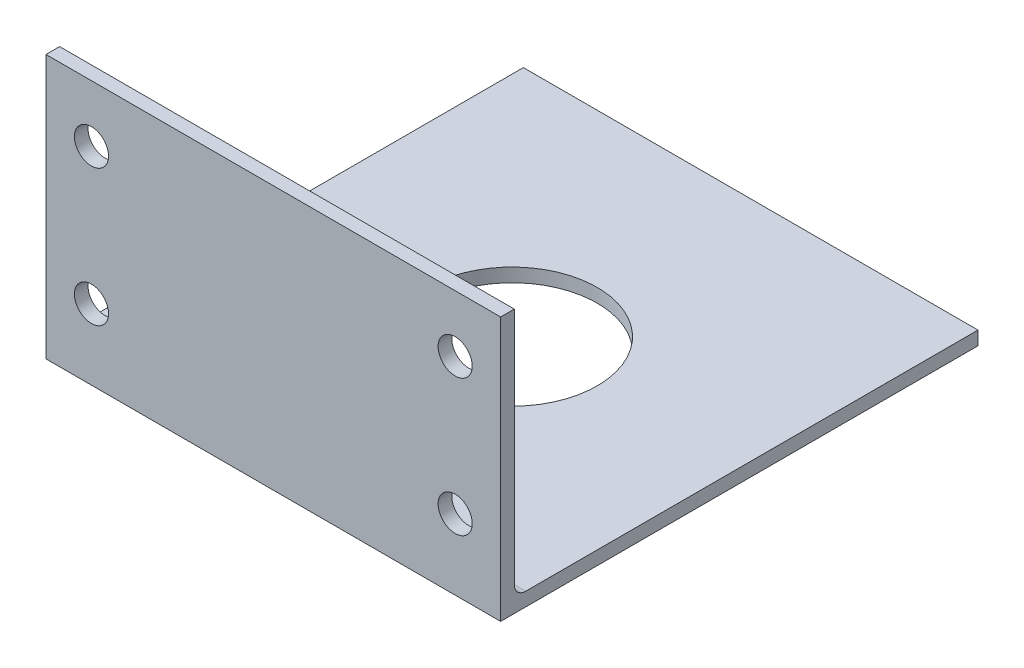
SolidWorks part; units mm, degrees
ref_plane "Front Plane" through (0, 0, 0) normal (0, 0, 1) x (1, 0, 0)
ref_plane "Top Plane" through (0, 0, 0) normal (0, 1, 0) x (1, 0, 0)
ref_plane "Right Plane" through (0, 0, 0) normal (1, 0, 0) x (0, 0, -1)
sketch "Sketch1" plane through (0, 0, 0) normal (0, 1, 0) x (1, 0, 0)
  line L1 (0, 0) -> (40, 0)
  line L2 (0, 0) -> (0, 42)
  line L3 (0, 42) -> (40, 42)
  line L4 (40, 0) -> (40, 42)
  dimension "D1" = 42
  dimension "D2" = 40
extrude "Boss-Extrude1" add sketch "Sketch1" along normal mid plane 1.2
sketch "Sketch3" plane through (0, 0.6, 0) normal (0, 1, 0) x (1, 0, 0)
  circle A0 centre (20, 21) radius 7.5
  dimension "D1" = 15
extrude "Cut-Extrude1" cut sketch "Sketch3" against normal through all
sketch "Sketch4" plane through (0, 0.6, 0) normal (0, 1, 0) x (1, 0, 0)
  line L0 (40, 0) -> (40, 42) construction
  line L1 (0, 0) -> (40, 0)
  line L2 (0, 0) -> (0, 1.2)
  line L3 (0, 1.2) -> (40, 1.2)
  line L4 (40, 0) -> (40, 1.2)
  dimension "D1" = 1.2
extrude "Boss-Extrude2" add sketch "Sketch4" along normal blind 22
sketch "Sketch5" plane through (0, 0, -1.2) normal (0, 0, -1) x (-1, 0, 0)
  line L0 (-40, 22.6) -> (-40, 0.6) construction
  line L1 (-40, 22.6) -> (0, 22.6) construction
  line L2 (-40, 0.6) -> (0, 0.6) construction
  line L3 (0, 22.6) -> (0, 0.6) construction
  circle A0 centre (-36, 17.6) radius 1.5
  circle A1 centre (-36, 5.6) radius 1.5
  circle A2 centre (-4, 17.6) radius 1.5
  circle A3 centre (-4, 5.6) radius 1.5
  point P14 (0, 0)
  dimension "D1" = 3
  dimension "D2" = 3
  dimension "D3" = 3
  dimension "D4" = 3
  dimension "D5" = 4
  dimension "D6" = 5
  dimension "D7" = 4
  dimension "D8" = 5
  dimension "D9" = 4
  dimension "D10" = 5
  dimension "D11" = 4
  dimension "D12" = 5
extrude "Cut-Extrude2" cut sketch "Sketch5" against normal through all
fillet "Fillet1" radius 1 1 edges at (20, 0.6, -1.2)
